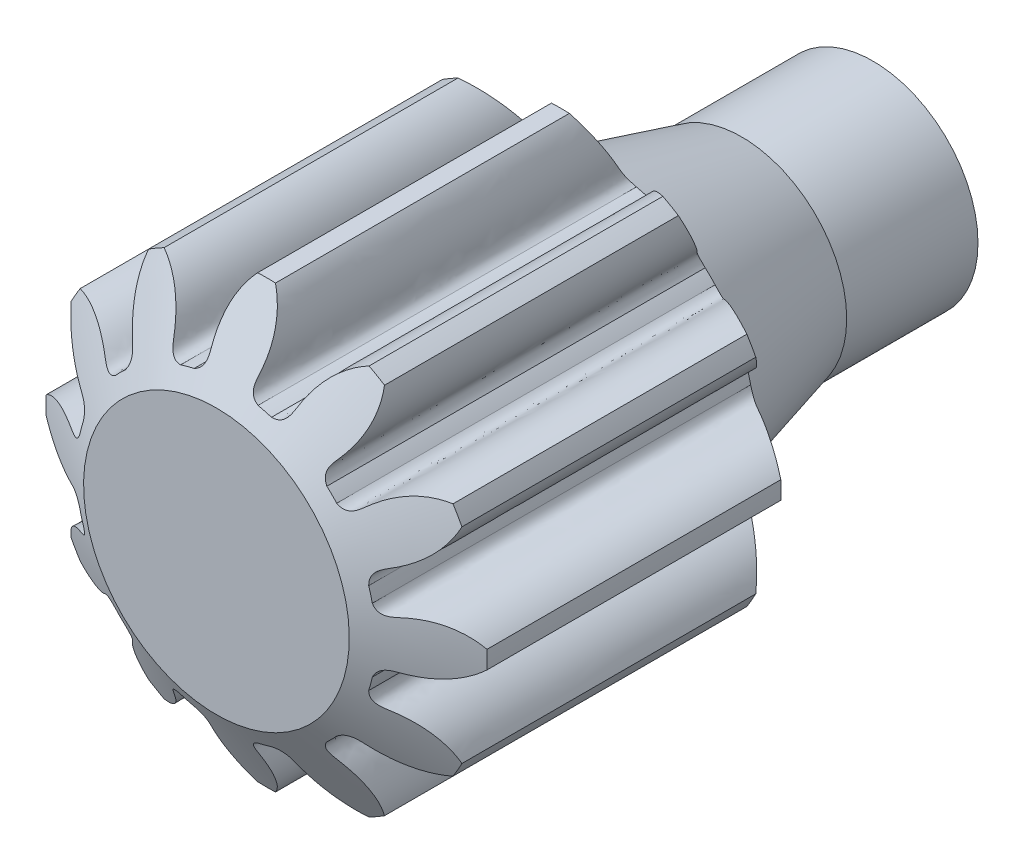
SolidWorks part; units mm, degrees
ref_plane "Front Plane" through (0, 0, 0) normal (0, 0, 1) x (1, 0, 0)
ref_plane "Top Plane" through (0, 0, 0) normal (0, 1, 0) x (1, 0, 0)
ref_plane "Right Plane" through (0, 0, 0) normal (1, 0, 0) x (0, 0, -1)
sketch "Sketch1" plane through (0, 0, 0) normal (0, 0, 1) x (1, 0, 0)
  line L0 (0, 0) -> (0, 11.2334) construction
  line L1 (0, 0) -> (2.9102, 10.861) construction
  circle A0 centre (0, 0) radius 8.4 construction
  arc A1 (0, 8.4) -> (0.3403, 8.3931) centre (0, 0) cw
  arc A2 (1.7293, 5.4313) -> (1.218, 5.5683) centre (0, 0) ccw
  arc A3 (4.2, 7.2746) -> (3.9018, 7.4388) centre (0, 0) ccw
  arc A4 (4.2, 7.2746) -> (4.4913, 7.0985) centre (0, 0) cw
  arc A5 (4.2133, 3.839) -> (3.839, 4.2133) centre (0, 0) ccw
  arc A6 (7.2746, 4.2) -> (7.0985, 4.4913) centre (0, 0) ccw
  arc A7 (7.2746, 4.2) -> (7.4388, 3.9018) centre (0, 0) cw
  arc A8 (5.5683, 1.218) -> (5.4313, 1.7293) centre (0, 0) ccw
  arc A9 (8.4, 0) -> (8.3931, 0.3403) centre (0, 0) ccw
  arc A10 (8.4, 0) -> (8.3931, -0.3403) centre (0, 0) cw
  arc A11 (5.4313, -1.7293) -> (5.5683, -1.218) centre (0, 0) ccw
  arc A12 (7.2746, -4.2) -> (7.4388, -3.9018) centre (0, 0) ccw
  arc A13 (7.2746, -4.2) -> (7.0985, -4.4913) centre (0, 0) cw
  arc A14 (3.839, -4.2133) -> (4.2133, -3.839) centre (0, 0) ccw
  arc A15 (4.2, -7.2746) -> (4.4913, -7.0985) centre (0, 0) ccw
  arc A16 (4.2, -7.2746) -> (3.9018, -7.4388) centre (0, 0) cw
  arc A17 (1.218, -5.5683) -> (1.7293, -5.4313) centre (0, 0) ccw
  arc A18 (0, -8.4) -> (0.3403, -8.3931) centre (0, 0) ccw
  arc A19 (0, -8.4) -> (-0.3403, -8.3931) centre (0, 0) cw
  arc A20 (-1.7293, -5.4313) -> (-1.218, -5.5683) centre (0, 0) ccw
  arc A21 (-4.2, -7.2746) -> (-3.9018, -7.4388) centre (0, 0) ccw
  arc A22 (-4.2, -7.2746) -> (-4.4913, -7.0985) centre (0, 0) cw
  arc A23 (-4.2133, -3.839) -> (-3.839, -4.2133) centre (0, 0) ccw
  arc A24 (-7.2746, -4.2) -> (-7.0985, -4.4913) centre (0, 0) ccw
  arc A25 (-7.2746, -4.2) -> (-7.4388, -3.9018) centre (0, 0) cw
  arc A26 (-5.5683, -1.218) -> (-5.4313, -1.7293) centre (0, 0) ccw
  arc A27 (-8.4, 0) -> (-8.3931, -0.3403) centre (0, 0) ccw
  arc A28 (-8.4, 0) -> (-8.3931, 0.3403) centre (0, 0) cw
  arc A29 (-5.4313, 1.7293) -> (-5.5683, 1.218) centre (0, 0) ccw
  arc A30 (-7.2746, 4.2) -> (-7.4388, 3.9018) centre (0, 0) ccw
  arc A31 (-7.2746, 4.2) -> (-7.0985, 4.4913) centre (0, 0) cw
  arc A32 (-3.839, 4.2133) -> (-4.2133, 3.839) centre (0, 0) ccw
  arc A33 (-4.2, 7.2746) -> (-4.4913, 7.0985) centre (0, 0) ccw
  arc A34 (-4.2, 7.2746) -> (-3.9018, 7.4388) centre (0, 0) cw
  arc A35 (-1.218, 5.5683) -> (-1.7293, 5.4313) centre (0, 0) ccw
  arc A36 (0, 8.4) -> (-0.3403, 8.3931) centre (0, 0) ccw
  spline S0 degree 3 poles (0.3403, 8.3931) (0.8434, 7.829) (1.0957, 6.7884) (0.7935, 5.7523) (1.218, 5.5683) knots 0 0 0 0 0.704221 1 1 1 1
  spline S1 degree 3 poles (3.9018, 7.4388) (3.1841, 7.2018) (2.4453, 6.4267) (2.189, 5.3784) (1.7293, 5.4313) knots 0 0 0 0 0.704221 1 1 1 1
  spline S2 degree 3 poles (4.4913, 7.0985) (4.6449, 6.3584) (4.3431, 5.3311) (3.5634, 4.5849) (3.839, 4.2133) knots 0 0 0 0 0.704221 1 1 1 1
  spline S3 degree 3 poles (7.0985, 4.4913) (6.3584, 4.6449) (5.3311, 4.3431) (4.5849, 3.5634) (4.2133, 3.839) knots 0 0 0 0 0.704221 1 1 1 1
  spline S4 degree 3 poles (7.4388, 3.9018) (7.2018, 3.1841) (6.4267, 2.4453) (5.3784, 2.189) (5.4313, 1.7293) knots 0 0 0 0 0.704221 1 1 1 1
  spline S5 degree 3 poles (8.3931, 0.3403) (7.829, 0.8434) (6.7884, 1.0957) (5.7523, 0.7935) (5.5683, 1.218) knots 0 0 0 0 0.704221 1 1 1 1
  spline S6 degree 3 poles (8.3931, -0.3403) (7.829, -0.8434) (6.7884, -1.0957) (5.7523, -0.7935) (5.5683, -1.218) knots 0 0 0 0 0.704221 1 1 1 1
  spline S7 degree 3 poles (7.4388, -3.9018) (7.2018, -3.1841) (6.4267, -2.4453) (5.3784, -2.189) (5.4313, -1.7293) knots 0 0 0 0 0.704221 1 1 1 1
  spline S8 degree 3 poles (7.0985, -4.4913) (6.3584, -4.6449) (5.3311, -4.3431) (4.5849, -3.5634) (4.2133, -3.839) knots 0 0 0 0 0.704221 1 1 1 1
  spline S9 degree 3 poles (4.4913, -7.0985) (4.6449, -6.3584) (4.3431, -5.3311) (3.5634, -4.5849) (3.839, -4.2133) knots 0 0 0 0 0.704221 1 1 1 1
  spline S10 degree 3 poles (3.9018, -7.4388) (3.1841, -7.2018) (2.4453, -6.4267) (2.189, -5.3784) (1.7293, -5.4313) knots 0 0 0 0 0.704221 1 1 1 1
  spline S11 degree 3 poles (0.3403, -8.3931) (0.8434, -7.829) (1.0957, -6.7884) (0.7935, -5.7523) (1.218, -5.5683) knots 0 0 0 0 0.704221 1 1 1 1
  spline S12 degree 3 poles (-0.3403, -8.3931) (-0.8434, -7.829) (-1.0957, -6.7884) (-0.7935, -5.7523) (-1.218, -5.5683) knots 0 0 0 0 0.704221 1 1 1 1
  spline S13 degree 3 poles (-3.9018, -7.4388) (-3.1841, -7.2018) (-2.4453, -6.4267) (-2.189, -5.3784) (-1.7293, -5.4313) knots 0 0 0 0 0.704221 1 1 1 1
  spline S14 degree 3 poles (-4.4913, -7.0985) (-4.6449, -6.3584) (-4.3431, -5.3311) (-3.5634, -4.5849) (-3.839, -4.2133) knots 0 0 0 0 0.704221 1 1 1 1
  spline S15 degree 3 poles (-7.0985, -4.4913) (-6.3584, -4.6449) (-5.3311, -4.3431) (-4.5849, -3.5634) (-4.2133, -3.839) knots 0 0 0 0 0.704221 1 1 1 1
  spline S16 degree 3 poles (-7.4388, -3.9018) (-7.2018, -3.1841) (-6.4267, -2.4453) (-5.3784, -2.189) (-5.4313, -1.7293) knots 0 0 0 0 0.704221 1 1 1 1
  spline S17 degree 3 poles (-8.3931, -0.3403) (-7.829, -0.8434) (-6.7884, -1.0957) (-5.7523, -0.7935) (-5.5683, -1.218) knots 0 0 0 0 0.704221 1 1 1 1
  spline S18 degree 3 poles (-8.3931, 0.3403) (-7.829, 0.8434) (-6.7884, 1.0957) (-5.7523, 0.7935) (-5.5683, 1.218) knots 0 0 0 0 0.704221 1 1 1 1
  spline S19 degree 3 poles (-7.4388, 3.9018) (-7.2018, 3.1841) (-6.4267, 2.4453) (-5.3784, 2.189) (-5.4313, 1.7293) knots 0 0 0 0 0.704221 1 1 1 1
  spline S20 degree 3 poles (-7.0985, 4.4913) (-6.3584, 4.6449) (-5.3311, 4.3431) (-4.5849, 3.5634) (-4.2133, 3.839) knots 0 0 0 0 0.704221 1 1 1 1
  spline S21 degree 3 poles (-4.4913, 7.0985) (-4.6449, 6.3584) (-4.3431, 5.3311) (-3.5634, 4.5849) (-3.839, 4.2133) knots 0 0 0 0 0.704221 1 1 1 1
  spline S22 degree 3 poles (-3.9018, 7.4388) (-3.1841, 7.2018) (-2.4453, 6.4267) (-2.189, 5.3784) (-1.7293, 5.4313) knots 0 0 0 0 0.704221 1 1 1 1
  spline S23 degree 3 poles (-0.3403, 8.3931) (-0.8434, 7.829) (-1.0957, 6.7884) (-0.7935, 5.7523) (-1.218, 5.5683) knots 0 0 0 0 0.704221 1 1 1 1
  point P153 (0, 0)
  dimension "D1" = 16.8
  dimension "D3" = 8.4
  dimension "D4" = 5.7
  dimension "D2" = 15
  dimension "D5" = 12
extrude "Boss-Extrude1" add sketch "Sketch1" along normal mid plane 15 contours A36 S23 A35 S22 A34 A33 S21 A32 S20 A31 A30 S19 A29 S18 A28 A27 S17 A26 S16 A25 A24 S15 A23 S14 A22 A21 S13 A20 S12 A19 A18 S11 A17 S10 A16 A15 S9 A14 S8 A13 A12 S7 A11 S6 A10 A9 S5 A8 S4 A7 A6
sketch "Sketch2" plane through (0, 0, 0) normal (1, 0, 0) x (0, 0, -1)
  line L0 (-7.5, 5.0592) -> (-5.5, 8.5592)
  line L1 (-5.5, 8.5592) -> (5.5, 8.5592) construction
  line L2 (5.5, 8.5592) -> (7.5, 5.3367)
  line L5 (7.5, 5.3367) -> (7.5, 0) construction
  line L6 (7.5, 0) -> (-7.5, 0) construction
  line L7 (-7.5, 0) -> (-7.5, 5.0592) construction
  line L8 (-7.5, 7.0985) -> (-7.5, 4.2133) construction
  line L9 (7.5, 4.2133) -> (7.5, 7.0985) construction
  line L11 (-7.5, 5.0592) -> (-7.5, 8.5592)
  line L12 (-7.5, 8.5592) -> (-5.5, 8.5592)
  line L13 (5.5, 8.5592) -> (7.5, 8.5592)
  line L14 (7.5, 8.5592) -> (7.5, 5.3367)
  dimension "D1" = 2
  dimension "D2" = 2
  dimension "D3" = 3.5
revolve "Cut-Revolve1" cut sketch "Sketch2" angle 360 about L6
sketch "Sketch4" plane through (0, 0, 0) normal (1, 0, 0) x (0, 0, -1)
  line L0 (0, 0) -> (21.4113, 0) construction
  line L1 (7.5, 5.3367) -> (12.5, 4)
  line L2 (12.5, 4) -> (17.5, 4)
  line L3 (17.5, 4) -> (17.5, 0)
  line L4 (7.5, 5.3367) -> (7.5, 0)
  line L5 (7.5, 0) -> (17.5, 0)
  dimension "D1" = 5
  dimension "D2" = 5
  dimension "D3" = 4
revolve "Revolve1" add sketch "Sketch4" angle 360 about L0
sketch "Sketch5" plane through (0, 0, -17.5) normal (0, 0, -1) x (-1, 0, 0)
  circle A0 centre (0, 0) radius 3
  dimension "D1" = 6
extrude "Cut-Extrude1" cut sketch "Sketch5" against normal blind 20
